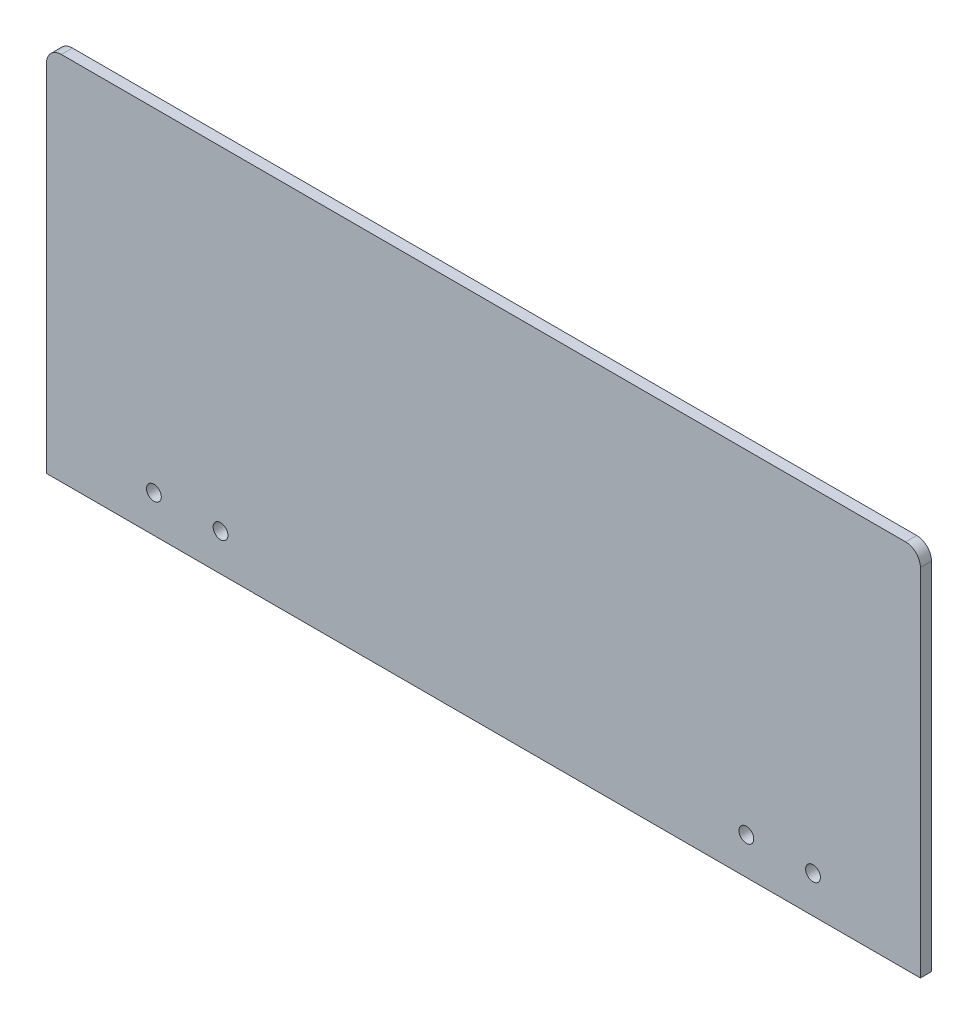
SolidWorks part; units mm, degrees
ref_plane "Plan de face" through (0, 0, 0) normal (0, 0, 1) x (1, 0, 0)
ref_plane "Plan de dessus" through (0, 0, 0) normal (0, 1, 0) x (1, 0, 0)
ref_plane "Plan de droite" through (0, 0, 0) normal (1, 0, 0) x (0, 0, -1)
sketch "Esquisse1" plane through (0, 0, 0) normal (0, 0, 1) x (1, 0, 0)
  line L0 (0, 0) -> (118, 0) construction
  line L1 (0, 0) -> (-118, 0) construction
  line L2 (-118, 0) -> (-118, -55) construction
  line L3 (-118, -55) -> (118, -55)
  line L4 (118, -55) -> (118, -155)
  line L5 (118, -155) -> (-118, -155)
  line L7 (-118, -55) -> (-118, -155)
  dimension "D2" = 118
  dimension "D4" = 100
extrude "Boss.-Extru.1" add sketch "Esquisse1" along normal blind 3
sketch "Esquisse3" plane through (0, 0, 3) normal (0, 0, 1) x (1, 0, 0)
  line L0 (0, -155) -> (-80, -155) construction
  line L1 (-118, -155) -> (118, -155) construction
  line L2 (-80, -155) -> (-80, -145) construction
  line L3 (-80, -145) -> (-71, -145) construction
  line L4 (-80, -145) -> (-89, -145) construction
  circle A0 centre (-71, -145) radius 2
  circle A1 centre (-89, -145) radius 2
  dimension "D3" = 9
  dimension "D1" = 10
  dimension "D2" = 9
extrude "Enlèv. mat.-Extru.1" cut sketch "Esquisse3" against normal up to next
mirror "Symétrie1" about plane through (0, 0, 0) normal (1, 0, 0) of "Enlèv. mat.-Extru.1"
fillet "Congé1" radius 4 2 edges at (118, -55, 1.5) (-118, -55, 1.5)
